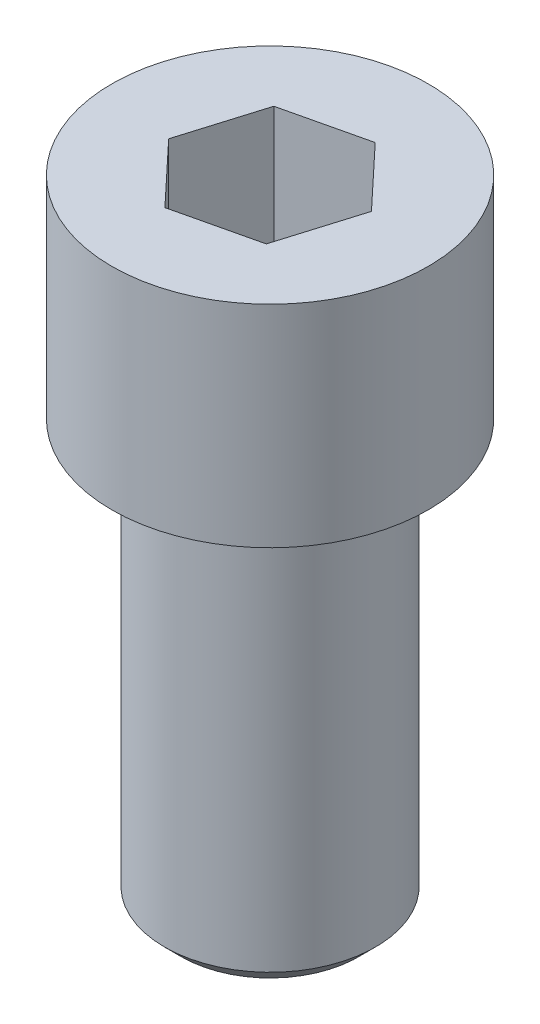
SolidWorks part; units mm, degrees
ref_plane "Front Plane" through (0, 0, 0) normal (0, 0, 1) x (1, 0, 0)
ref_plane "Top Plane" through (0, 0, 0) normal (0, 1, 0) x (1, 0, 0)
ref_plane "Right Plane" through (0, 0, 0) normal (1, 0, 0) x (0, 0, -1)
sketch "Sketch2" plane through (0, 0, 0) normal (0, 1, 0) x (1, 0, 0)
  circle A0 centre (0, 0) radius 0.1875
  dimension "D1" = 0.375
extrude "Boss-Extrude2" add sketch "Sketch2" along normal blind 0.75
ref_plane "Plane1" through (0, 0.75, 0) normal (0, 1, 0) x (1, 0, 0)
sketch "Sketch3" plane through (0, 0.75, 0) normal (0, 1, 0) x (1, 0, 0)
  line L1 (0.0684, -0.0729) -> (0.0974, 0.0228)
  line L2 (0.0974, 0.0228) -> (0.0289, 0.0957)
  line L3 (0.0289, 0.0957) -> (-0.0684, 0.0729)
  line L4 (-0.0684, 0.0729) -> (-0.0974, -0.0228)
  line L5 (-0.0974, -0.0228) -> (-0.0289, -0.0957)
  line L6 (-0.0289, -0.0957) -> (0.0684, -0.0729)
  circle A0 centre (0, 0) radius 0.0866 construction
  dimension "D1" = 0.2
extrude "Cut-Extrude1" cut sketch "Sketch3" against normal blind 0.15
sketch "Sketch4" plane through (0, 0, 0) normal (0, 1, 0) x (1, 0, 0)
  circle A0 centre (0, 0) radius 0.125
  circle A2 centre (0, 0) radius 0.1875
  circle A3 centre (0, 0) radius 0.1875
  dimension "D1" = 0.25
  dimension "D2" = 0
extrude "Cut-Extrude2" cut sketch "Sketch4" along normal blind 0.5
chamfer "Chamfer1" distance 0.02 angle 45 1 edges at (0, 0, 0.125)
fillet "Fillet1" radius 0.015 1 edges at (0, 0.5, 0.125)
